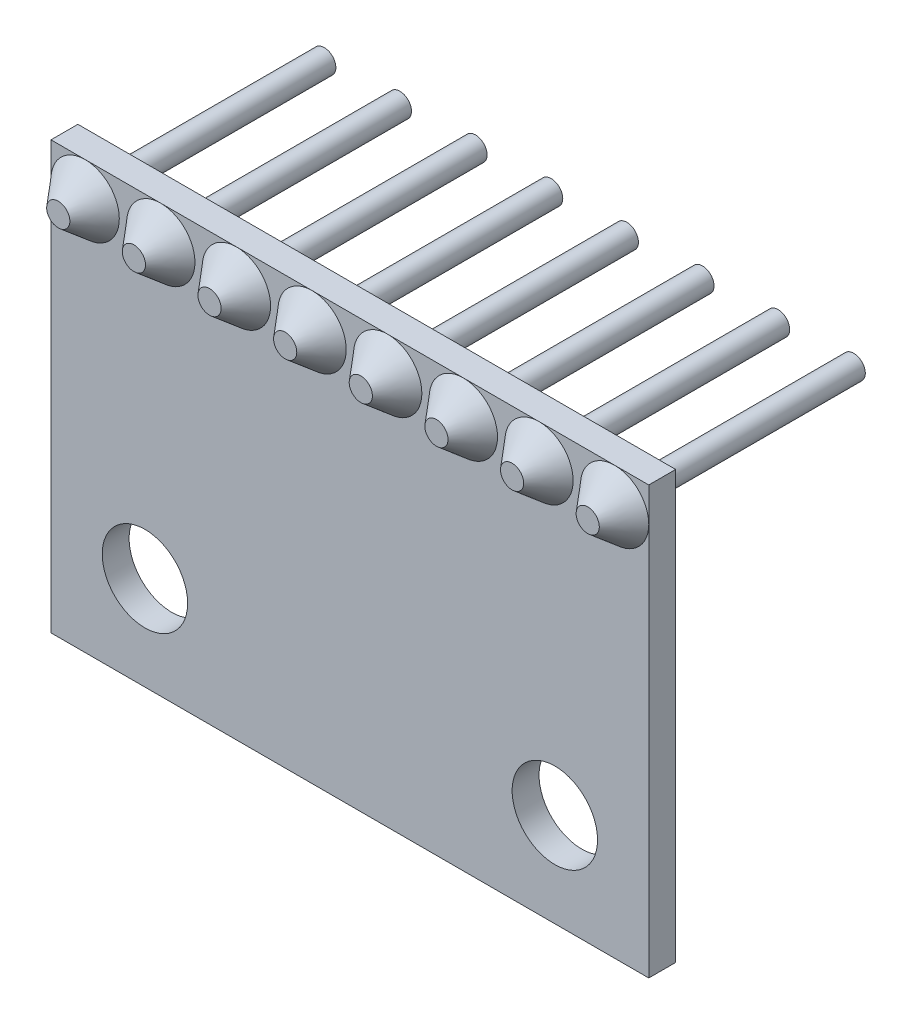
SolidWorks part; units mm, degrees
ref_plane "Front Plane" through (0, 0, 0) normal (0, 0, 1) x (1, 0, 0)
ref_plane "Top Plane" through (0, 0, 0) normal (0, 1, 0) x (1, 0, 0)
ref_plane "Right Plane" through (0, 0, 0) normal (1, 0, 0) x (0, 0, -1)
sketch "Sketch1" plane through (0, 0, 0) normal (0, 0, 1) x (1, 0, 0)
  line L0 (-18.7325, 3.4925) -> (-3.4925, 3.4925) construction
  line L1 (0, 0) -> (-22.225, 0)
  line L2 (0, 0) -> (0, 15.875)
  line L3 (0, 15.875) -> (-22.225, 15.875)
  line L4 (-22.225, 0) -> (-22.225, 15.875)
  line L5 (-3.4925, 3.4925) -> (0, 3.4925) construction
  line L6 (-18.7325, 3.4925) -> (-18.7325, 0) construction
  line L8 (-22.225, 3.4925) -> (-18.7325, 3.4925) construction
  circle A0 centre (-18.7325, 3.4925) radius 1.5875
  circle A1 centre (-3.4925, 3.4925) radius 1.5875
  dimension "D2" = 3.175
  dimension "D1" = 15.24
  dimension "D3" = 22.225
  dimension "D4" = 15.875
extrude "Boss-Extrude1" add sketch "Sketch1" along normal blind 1
sketch "Sketch2" plane through (0, 0, 0) normal (0, 0, 1) x (1, 0, 0)
  line L0 (-11.1125, 15.875) -> (-11.1125, 0) construction
  line L1 (0, 15.875) -> (-22.225, 15.875) construction
  line L2 (-22.225, 0) -> (0, 0) construction
  line L3 (-9.6125, 11.8127) -> (-12.6125, 11.8127)
  line L4 (-12.6125, 11.8127) -> (-12.6125, 7.8127)
  line L5 (-12.6125, 7.8127) -> (-9.6125, 7.8127)
  line L6 (-9.6125, 11.8127) -> (-9.6125, 7.8127)
  point P11 (-11.1125, 7.8127)
  point P12 (-11.1125, 11.8127)
  dimension "D1" = 3
  dimension "D2" = 4
extrude "Boss-Extrude2" add sketch "Sketch2" against normal blind 1
sketch "Sketch3" plane through (0, 0, 1) normal (0, 0, 1) x (1, 0, 0)
  line L0 (-20.955, 14.605) -> (-22.225, 14.605) construction
  line L3 (-22.225, 15.875) -> (-22.225, 0) construction
  line L4 (-20.955, 15.875) -> (-20.955, 14.605) construction
  line L5 (0, 15.875) -> (-22.225, 15.875) construction
  line L6 (-20.955, 14.605) -> (-1.27, 14.605) construction
  line L7 (-1.27, 14.605) -> (0, 14.605) construction
  line L8 (0, 0) -> (0, 15.875) construction
  line L10 (-1.27, 15.875) -> (-1.27, 14.605) construction
  circle A0 centre (-20.955, 14.605) radius 1.27
  circle A1 centre (-18.1429, 14.605) radius 1.27
  circle A2 centre (-15.3307, 14.605) radius 1.27
  circle A3 centre (-12.5186, 14.605) radius 1.27
  circle A4 centre (-9.7064, 14.605) radius 1.27
  circle A5 centre (-6.8943, 14.605) radius 1.27
  circle A6 centre (-4.0821, 14.605) radius 1.27
  circle A7 centre (-1.27, 14.605) radius 1.27
  dimension "D2" = 2.54
  dimension "D3" = 1.27
  dimension "D1" = 8
extrude "Boss-Extrude3" add sketch "Sketch3" along normal blind 1 draft 40
sketch "Sketch4" plane through (0, 0, 2) normal (0, 0, 1) x (1, 0, 0)
  circle A0 centre (-20.955, 14.605) radius 0.4309 construction
  circle A1 centre (-18.1429, 14.605) radius 0.4309 construction
  circle A2 centre (-15.3307, 14.605) radius 0.4309 construction
  circle A3 centre (-12.5186, 14.605) radius 0.4309 construction
  circle A4 centre (-9.7064, 14.605) radius 0.4309 construction
  circle A5 centre (-6.8943, 14.605) radius 0.4309 construction
  circle A6 centre (-4.0821, 14.605) radius 0.4309 construction
  circle A7 centre (-1.27, 14.605) radius 0.4309 construction
  circle A8 centre (-20.955, 14.605) radius 0.4309
  circle A9 centre (-18.1429, 14.605) radius 0.4309
  circle A10 centre (-15.3307, 14.605) radius 0.4309
  circle A11 centre (-12.5186, 14.605) radius 0.4309
  circle A12 centre (-9.7064, 14.605) radius 0.4309
  circle A13 centre (-6.8943, 14.605) radius 0.4309
  circle A14 centre (-4.0821, 14.605) radius 0.4309
  circle A15 centre (-1.27, 14.605) radius 0.4309
extrude "Boss-Extrude4" add sketch "Sketch4" against normal blind 9.89
